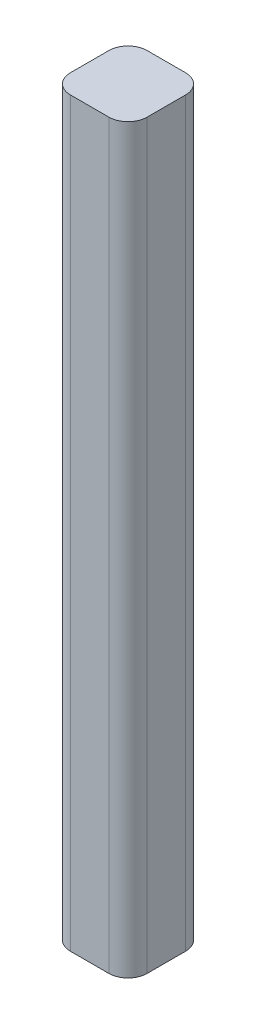
SolidWorks part; units mm, degrees
ref_plane "Plano frontal" through (0, 0, 0) normal (0, 0, 1) x (1, 0, 0)
ref_plane "Plano superior" through (0, 0, 0) normal (0, 1, 0) x (1, 0, 0)
ref_plane "Plano direito" through (0, 0, 0) normal (1, 0, 0) x (0, 0, -1)
sketch "Esboço1" plane through (0, 0, 0) normal (0, 1, 0) x (1, 0, 0)
  line L1 (-2, -4) -> (2, -4)
  line L2 (-4, -2) -> (-4, 2)
  line L3 (-2, 4) -> (2, 4)
  line L4 (4, -2) -> (4, 2)
  line L5 (-4, -4) -> (4, 4) construction
  line L6 (-4, 4) -> (4, -4) construction
  arc A0 (2, 4) -> (4, 2) centre (2, 2) cw
  arc A1 (4, -2) -> (2, -4) centre (2, -2) cw
  arc A2 (-2, -4) -> (-4, -2) centre (-2, -2) cw
  arc A3 (-4, 2) -> (-2, 4) centre (-2, 2) cw
  point P0 (0, 0)
  dimension "D3" = 2
  dimension "D1" = 8
  dimension "D2" = 8
extrude "Ressalto-extrusão1" add sketch "Esboço1" along normal blind 77.25
